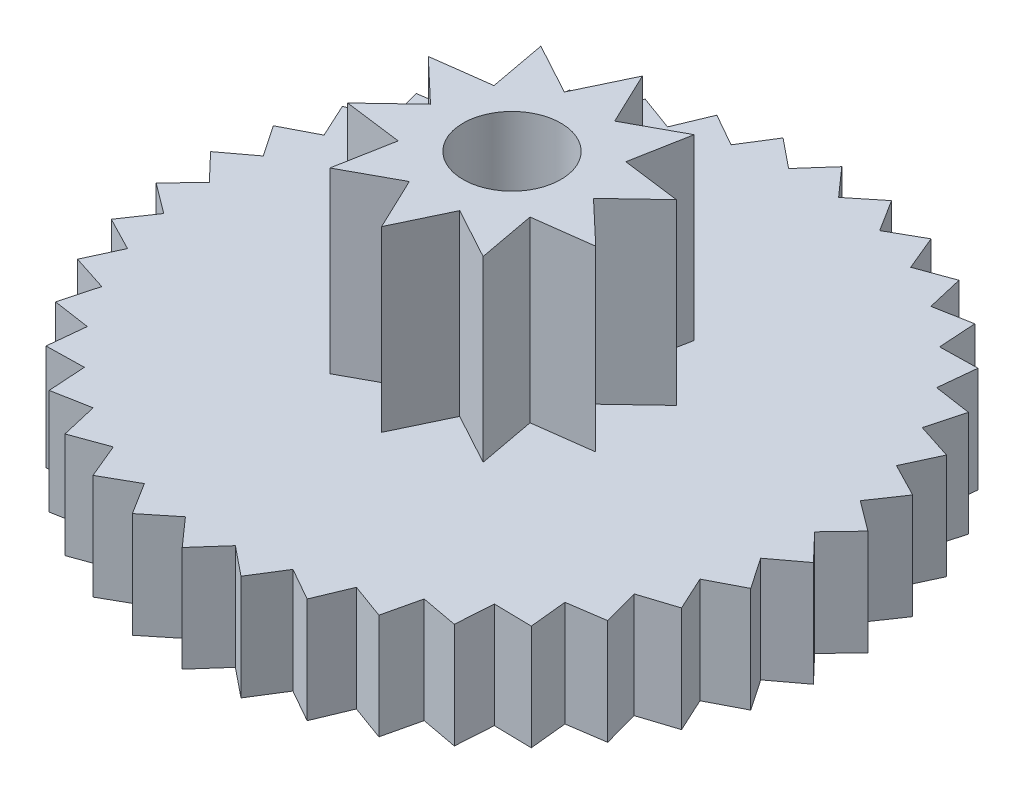
SolidWorks part; units mm, degrees
ref_plane "Front Plane" through (0, 0, 0) normal (0, 0, 1) x (1, 0, 0)
ref_plane "Top Plane" through (0, 0, 0) normal (0, 1, 0) x (1, 0, 0)
ref_plane "Right Plane" through (0, 0, 0) normal (1, 0, 0) x (0, 0, -1)
sketch "Sketch1" plane through (0, 0, 0) normal (0, 0, 1) x (1, 0, 0)
  line L0 (0, 5.22) -> (0, 1)
  line L1 (0, -55) -> (0, 55) construction
  line L2 (4.45, 0) -> (6.07, 0)
  line L3 (55, 0) -> (-55, 0) construction
  line L4 (6.07, 0) -> (6.07, 1.94)
  line L5 (6.07, 1.94) -> (2.4, 1.94)
  line L6 (2.4, 1.94) -> (2.4, 5.22)
  line L7 (2.4, 5.22) -> (0, 5.22)
  line L8 (4.45, 0) -> (4.45, 0.42)
  line L9 (4.45, 0.42) -> (2.72, 0.42)
  line L10 (2.72, 0.42) -> (2.72, 1)
  line L11 (2.72, 1) -> (0, 1)
  dimension "D1" = 2.4
  dimension "D2" = 4.45
  dimension "D3" = 3.28
  dimension "D4" = 1.94
  dimension "D5" = 2.72
  dimension "D6" = 0.42
  dimension "D7" = 1
  dimension "D8" = 6.07
revolve "Revolve1" add sketch "Sketch1" angle 360 about L0
sketch "Sketch2" plane through (0, 1.94, 0) normal (0, 1, 0) x (1, 0, 0)
  line L0 (0, 6.07) -> (-0.46, 5.551)
  line L1 (0, -2.871) -> (0, 2.871) construction
  line L2 (-0.46, 5.551) -> (0, 0) construction
  line L3 (0, 0) -> (0.46, 5.551) construction
  line L4 (0.46, 5.551) -> (0, 6.07)
  line L5 (0.9991, 5.9872) -> (0.46, 5.551)
  line L6 (1.3674, 5.3996) -> (0.9991, 5.9872)
  line L7 (1.9709, 5.7411) -> (1.3674, 5.3996)
  line L8 (2.2374, 5.1009) -> (1.9709, 5.7411)
  line L9 (2.889, 5.3384) -> (2.2374, 5.1009)
  line L10 (3.0465, 4.663) -> (2.889, 5.3384)
  line L11 (3.7283, 4.7901) -> (3.0465, 4.663)
  line L12 (3.7725, 4.098) -> (3.7283, 4.7901)
  line L13 (4.4658, 4.1111) -> (3.7725, 4.098)
  line L14 (4.3955, 3.4212) -> (4.4658, 4.1111)
  line L15 (5.0816, 3.32) -> (4.3955, 3.4212)
  line L16 (4.8987, 2.651) -> (5.0816, 3.32)
  line L17 (5.5587, 2.4383) -> (4.8987, 2.651)
  line L18 (5.2682, 1.8086) -> (5.5587, 2.4383)
  line L19 (5.8843, 1.4901) -> (5.2682, 1.8086)
  line L20 (5.494, 0.9168) -> (5.8843, 1.4901)
  line L21 (6.0493, 0.5013) -> (5.494, 0.9168)
  line L22 (5.57, 0) -> (6.0493, 0.5013)
  line L23 (6.0493, -0.5013) -> (5.57, 0)
  line L24 (5.494, -0.9168) -> (6.0493, -0.5013)
  line L25 (5.8843, -1.4901) -> (5.494, -0.9168)
  line L26 (5.2682, -1.8086) -> (5.8843, -1.4901)
  line L27 (5.5587, -2.4383) -> (5.2682, -1.8086)
  line L28 (4.8987, -2.651) -> (5.5587, -2.4383)
  line L29 (5.0816, -3.32) -> (4.8987, -2.651)
  line L30 (4.3955, -3.4212) -> (5.0816, -3.32)
  line L31 (4.4658, -4.1111) -> (4.3955, -3.4212)
  line L32 (3.7725, -4.098) -> (4.4658, -4.1111)
  line L33 (3.7283, -4.7901) -> (3.7725, -4.098)
  line L34 (3.0465, -4.663) -> (3.7283, -4.7901)
  line L35 (2.889, -5.3384) -> (3.0465, -4.663)
  line L36 (2.2374, -5.1009) -> (2.889, -5.3384)
  line L37 (1.9709, -5.7411) -> (2.2374, -5.1009)
  line L38 (1.3674, -5.3996) -> (1.9709, -5.7411)
  line L39 (0.9991, -5.9872) -> (1.3674, -5.3996)
  line L40 (0.46, -5.551) -> (0.9991, -5.9872)
  line L41 (0, -6.07) -> (0.46, -5.551)
  line L42 (-0.46, -5.551) -> (0, -6.07)
  line L43 (-0.9991, -5.9872) -> (-0.46, -5.551)
  line L44 (-1.3674, -5.3996) -> (-0.9991, -5.9872)
  line L45 (-1.9709, -5.7411) -> (-1.3674, -5.3996)
  line L46 (-2.2374, -5.1009) -> (-1.9709, -5.7411)
  line L47 (-2.889, -5.3384) -> (-2.2374, -5.1009)
  line L48 (-3.0465, -4.663) -> (-2.889, -5.3384)
  line L49 (-3.7283, -4.7901) -> (-3.0465, -4.663)
  line L50 (-3.7725, -4.098) -> (-3.7283, -4.7901)
  line L51 (-4.4658, -4.1111) -> (-3.7725, -4.098)
  line L52 (-4.3955, -3.4212) -> (-4.4658, -4.1111)
  line L53 (-5.0816, -3.32) -> (-4.3955, -3.4212)
  line L54 (-4.8987, -2.651) -> (-5.0816, -3.32)
  line L55 (-5.5587, -2.4383) -> (-4.8987, -2.651)
  line L56 (-5.2682, -1.8086) -> (-5.5587, -2.4383)
  line L57 (-5.8843, -1.4901) -> (-5.2682, -1.8086)
  line L58 (-5.494, -0.9168) -> (-5.8843, -1.4901)
  line L59 (-6.0493, -0.5013) -> (-5.494, -0.9168)
  line L60 (-5.57, 0) -> (-6.0493, -0.5013)
  line L61 (-6.0493, 0.5013) -> (-5.57, 0)
  line L62 (-5.494, 0.9168) -> (-6.0493, 0.5013)
  line L63 (-5.8843, 1.4901) -> (-5.494, 0.9168)
  line L64 (-5.2682, 1.8086) -> (-5.8843, 1.4901)
  line L65 (-5.5587, 2.4383) -> (-5.2682, 1.8086)
  line L66 (-4.8987, 2.651) -> (-5.5587, 2.4383)
  line L67 (-5.0816, 3.32) -> (-4.8987, 2.651)
  line L68 (-4.3955, 3.4212) -> (-5.0816, 3.32)
  line L69 (-4.4658, 4.1111) -> (-4.3955, 3.4212)
  line L70 (-3.7725, 4.098) -> (-4.4658, 4.1111)
  line L71 (-3.7283, 4.7901) -> (-3.7725, 4.098)
  line L72 (-3.0465, 4.663) -> (-3.7283, 4.7901)
  line L73 (-2.889, 5.3384) -> (-3.0465, 4.663)
  line L74 (-2.2374, 5.1009) -> (-2.889, 5.3384)
  line L75 (-1.9709, 5.7411) -> (-2.2374, 5.1009)
  line L76 (-1.3674, 5.3996) -> (-1.9709, 5.7411)
  line L77 (-0.9991, 5.9872) -> (-1.3674, 5.3996)
  line L78 (-0.46, 5.551) -> (-0.9991, 5.9872)
  circle A0 centre (0, 0) radius 5.57 construction
  circle A1 centre (0, 0) radius 6.07 construction
  circle A4 centre (0, 0) radius 6.57
  circle A5 centre (0, 0) radius 6.57
  point P127 (0, 0)
  dimension "D2" = 0.5
  dimension "D1" = 9.474
  dimension "D3" = 0.5
  dimension "D4" = 38
extrude "Cut-Extrude1" cut sketch "Sketch2" against normal through all
sketch "Sketch3" plane through (0, 5.22, 0) normal (0, 1, 0) x (1, 0, 0)
  line L0 (0, 2.4) -> (-0.4635, 1.4266)
  line L1 (0, -2.871) -> (0, 2.871) construction
  line L2 (-0.4635, 1.4266) -> (0, 0) construction
  line L3 (0, 0) -> (0.4635, 1.4266) construction
  line L4 (0.4635, 1.4266) -> (0, 2.4)
  line L5 (1.2135, 0.8817) -> (1.4107, 1.9416)
  line L6 (1.4107, 1.9416) -> (0.4635, 1.4266)
  line L7 (1.5, 0) -> (2.2825, 0.7416)
  line L8 (2.2825, 0.7416) -> (1.2135, 0.8817)
  line L9 (1.2135, -0.8817) -> (2.2825, -0.7416)
  line L10 (2.2825, -0.7416) -> (1.5, 0)
  line L11 (0.4635, -1.4266) -> (1.4107, -1.9416)
  line L12 (1.4107, -1.9416) -> (1.2135, -0.8817)
  line L13 (-0.4635, -1.4266) -> (0, -2.4)
  line L14 (0, -2.4) -> (0.4635, -1.4266)
  line L15 (-1.2135, -0.8817) -> (-1.4107, -1.9416)
  line L16 (-1.4107, -1.9416) -> (-0.4635, -1.4266)
  line L17 (-1.5, 0) -> (-2.2825, -0.7416)
  line L18 (-2.2825, -0.7416) -> (-1.2135, -0.8817)
  line L19 (-1.2135, 0.8817) -> (-2.2825, 0.7416)
  line L20 (-2.2825, 0.7416) -> (-1.5, 0)
  line L21 (-0.4635, 1.4266) -> (-1.4107, 1.9416)
  line L22 (-1.4107, 1.9416) -> (-1.2135, 0.8817)
  circle A0 centre (0, 0) radius 1.5 construction
  circle A1 centre (0, 0) radius 2.4 construction
  circle A4 centre (0, 0) radius 2.9
  circle A5 centre (0, 0) radius 2.9
  point P40 (0, 0)
  dimension "D1" = 3
  dimension "D2" = 36
  dimension "D4" = 0.5
  dimension "D3" = 10
extrude "Cut-Extrude2" cut sketch "Sketch3" against normal up to surface (3.28 mm away) up to face at (-2.4, 1.94, 0)
sketch "Sketch4" plane through (0, 5.22, 0) normal (0, 1, 0) x (1, 0, 0)
  circle A0 centre (0, 0) radius 0.9
  dimension "D1" = 1.8
extrude "Cut-Extrude3" cut sketch "Sketch4" against normal through all
